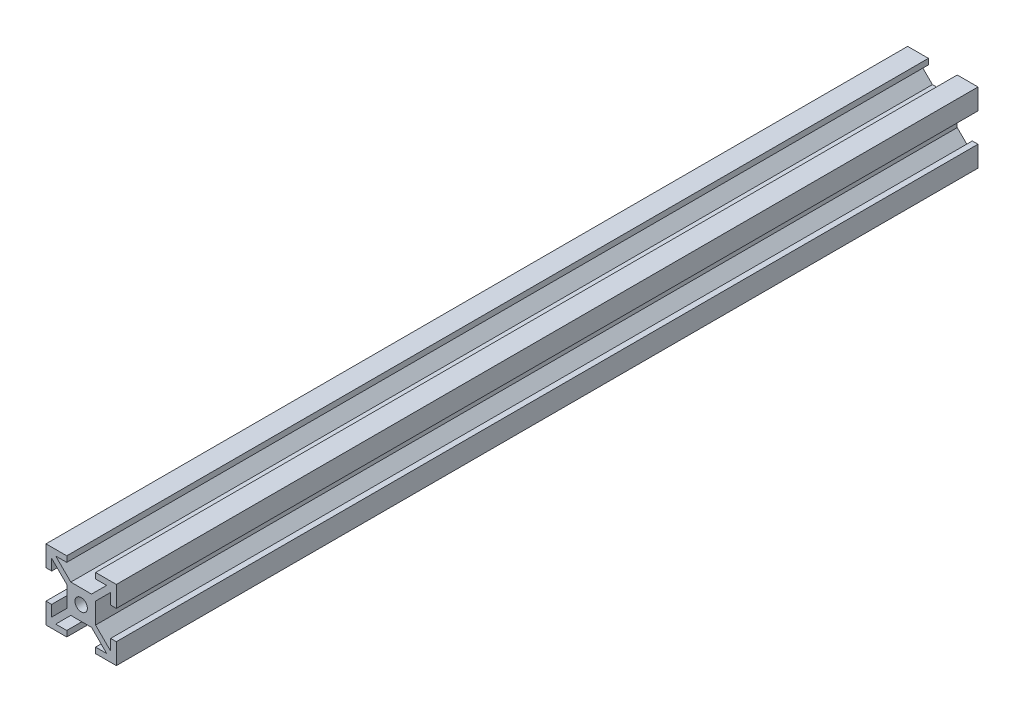
SolidWorks part; units mm, degrees
ref_plane "Front Plane" through (0, 0, 0) normal (0, 0, 1) x (1, 0, 0)
ref_plane "Top Plane" through (0, 0, 0) normal (0, 1, 0) x (1, 0, 0)
ref_plane "Right Plane" through (0, 0, 0) normal (1, 0, 0) x (0, 0, -1)
sketch "Sketch1" plane through (0, 0, 0) normal (0, 0, 1) x (1, 0, 0)
  line L0 (-8.38, 4.1) -> (-10, 4.1)
  line L1 (-2.9545, 4.1) -> (2.9545, 4.1)
  line L2 (-4.1, 2.9545) -> (-4.1, -2.9545)
  line L3 (-2.9545, -4.1) -> (2.9545, -4.1)
  line L4 (4.1, 2.9545) -> (4.1, -2.9545)
  line L5 (-4.1, 4.1) -> (4.1, -4.1) construction
  line L6 (-4.1, -4.1) -> (4.1, 4.1) construction
  line L7 (-10, 10) -> (-4.1, 10)
  line L8 (-10, 10) -> (-10, 4.1)
  line L9 (-10, -10) -> (-4.1, -10)
  line L10 (10, 10) -> (10, 4.1)
  line L11 (-10, 10) -> (10, -10) construction
  line L12 (-10, -10) -> (10, 10) construction
  line L13 (-7.2345, 8.38) -> (-4.1, 8.38)
  line L14 (-8.38, 7.2345) -> (-8.38, 4.1)
  line L15 (-7.2345, -8.38) -> (-4.1, -8.38)
  line L16 (8.38, 7.2345) -> (8.38, 4.1)
  line L17 (-8.38, 8.38) -> (8.38, -8.38) construction
  line L18 (-8.38, -8.38) -> (8.38, 8.38) construction
  line L19 (-4.1, 8.38) -> (-4.1, 10)
  line L20 (4.1, 10) -> (4.1, 8.38)
  line L21 (8.38, 4.1) -> (10, 4.1)
  line L22 (-8.38, -4.1) -> (-10, -4.1)
  line L23 (-4.1, -8.38) -> (-4.1, -10)
  line L24 (8.38, -4.1) -> (10, -4.1)
  line L25 (4.1, -8.38) -> (4.1, -10)
  line L26 (-5.464, 5.464) -> (-4.8912, 6.0368) construction
  line L27 (-4.1, 2.9545) -> (-8.38, 7.2345)
  line L28 (-2.9545, 4.1) -> (-7.2345, 8.38)
  line L29 (0, 11.3108) -> (0, -17.1823) construction
  line L30 (-16.7028, 0) -> (14.4032, 0) construction
  line L31 (-2.9545, -4.1) -> (-7.2345, -8.38)
  line L32 (-4.1, -2.9545) -> (-8.38, -7.2345)
  line L33 (2.9545, -4.1) -> (7.2345, -8.38)
  line L34 (4.1, -2.9545) -> (8.38, -7.2345)
  line L35 (4.1, 2.9545) -> (8.38, 7.2345)
  line L36 (2.9545, 4.1) -> (7.2345, 8.38)
  line L37 (4.1, 8.38) -> (7.2345, 8.38)
  line L38 (4.1, 10) -> (10, 10)
  line L39 (-8.38, -4.1) -> (-8.38, -7.2345)
  line L40 (-10, -4.1) -> (-10, -10)
  line L41 (8.38, -4.1) -> (8.38, -7.2345)
  line L42 (10, -4.1) -> (10, -10)
  line L43 (4.1, -8.38) -> (7.2345, -8.38)
  line L44 (4.1, -10) -> (10, -10)
  circle A0 centre (0, 0) radius 1.77
  point P0 (0, 0)
  point P6 (0, 0)
  dimension "D5" = 3.54
  dimension "D1" = 8.2
  dimension "D2" = 20
  dimension "D3" = 8.2
  dimension "D4" = 20
  dimension "D6" = 16.76
  dimension "D7" = 16.76
  dimension "D8" = 0.81
  dimension "D9" = 135
  dimension "D10" = 7.7696
  dimension "D11" = 5.0536
extrude "Boss-Extrude1" add sketch "Sketch1" along normal blind 245
